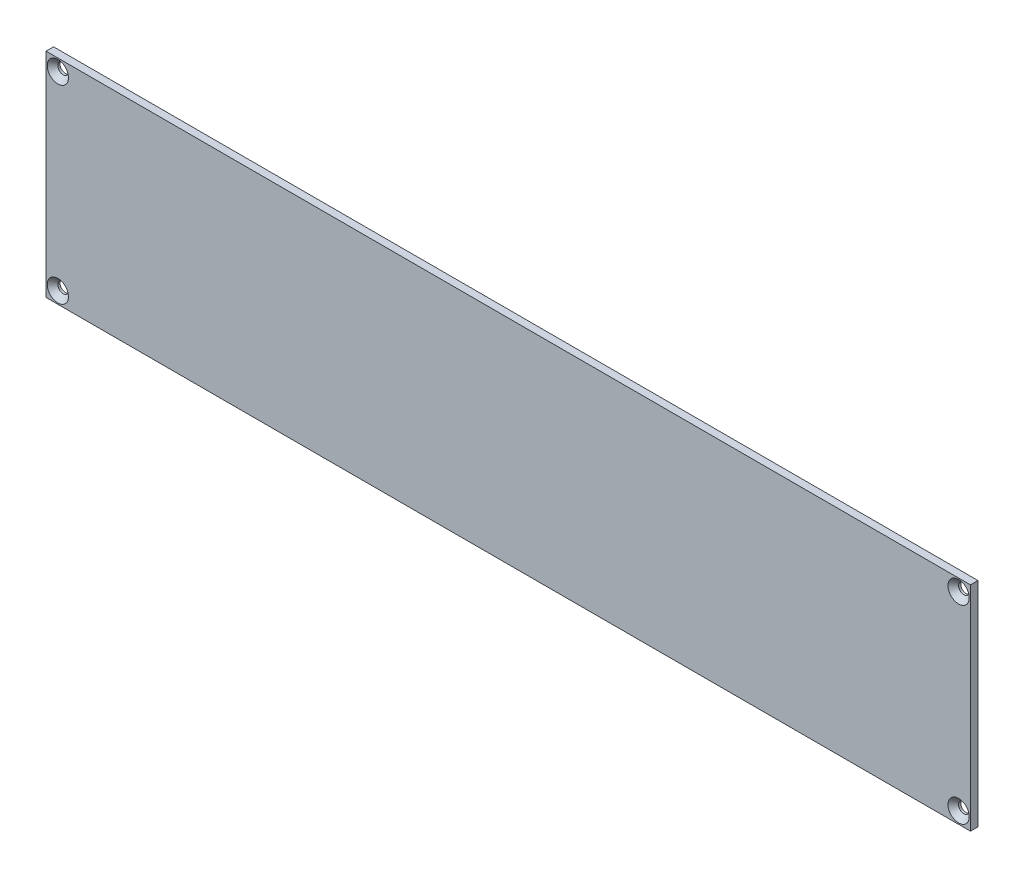
SolidWorks part; units mm, degrees
ref_plane "Front Plane" through (0, 0, 0) normal (0, 0, 1) x (1, 0, 0)
ref_plane "Top Plane" through (0, 0, 0) normal (0, 1, 0) x (1, 0, 0)
ref_plane "Right Plane" through (0, 0, 0) normal (1, 0, 0) x (0, 0, -1)
sketch "Sketch1" plane through (0, 0, 0) normal (0, 0, 1) x (1, 0, 0)
  line L1 (-195, -45) -> (195, -45)
  line L2 (-195, -45) -> (-195, 45)
  line L3 (-195, 45) -> (195, 45)
  line L4 (195, -45) -> (195, 45)
  line L5 (-195, -45) -> (195, 45) construction
  line L6 (-195, 45) -> (195, -45) construction
  point P0 (0, 0)
  dimension "D1" = 390
  dimension "D2" = 90
extrude "Boss-Extrude1" add sketch "Sketch1" along normal blind 3.175
hole_wizard "CSK for M4 SFHCS1" positions "Sketch2" profile "Sketch3" countersink size "M4" standard "ANSI Metric" end condition through all
sketch "Sketch2" plane through (0, 0, 3.175) normal (0, 0, 1) x (1, 0, 0)
  line L1 (-190, -40) -> (190, -40)
  line L2 (-190, -40) -> (-190, 40)
  line L3 (-190, 40) -> (190, 40)
  line L4 (190, -40) -> (190, 40)
  line L5 (-190, -40) -> (190, 40) construction
  line L6 (-190, 40) -> (190, -40) construction
  line L7 (195, -45) -> (195, 45) construction
  point P2 (190, 40)
  point P159 (-190, -40)
  point P160 (-190, 40)
  point P161 (190, -40)
  point P168 (0, 0)
  dimension "D1" = 5
  dimension "D2" = 5
sketch "Sketch3" plane through (190, 40, 3.175) normal (1, 0, 0) x (0, -1, 0)
  line L0 (0, 0) -> (0, 3.175)
  line L1 (0, 3.175) -> (2.25, 3.175)
  line L2 (2.25, 3.175) -> (2.25, 2.23)
  line L3 (2.25, 2.23) -> (4.48, 0)
  line L5 (4.48, 0) -> (0, 0)
  line L6 (-2.25, 2.23) -> (-4.48, 0) construction
  line L11 (0, -6.35) -> (0, 107.95) construction
  dimension "Thru Hole Dia." = 4.5
  dimension "Thru Hole Depth" = 3.175
  dimension "Near C'Sink Dia." = 8.96
  dimension "Near C'Sink Angle" = 90
